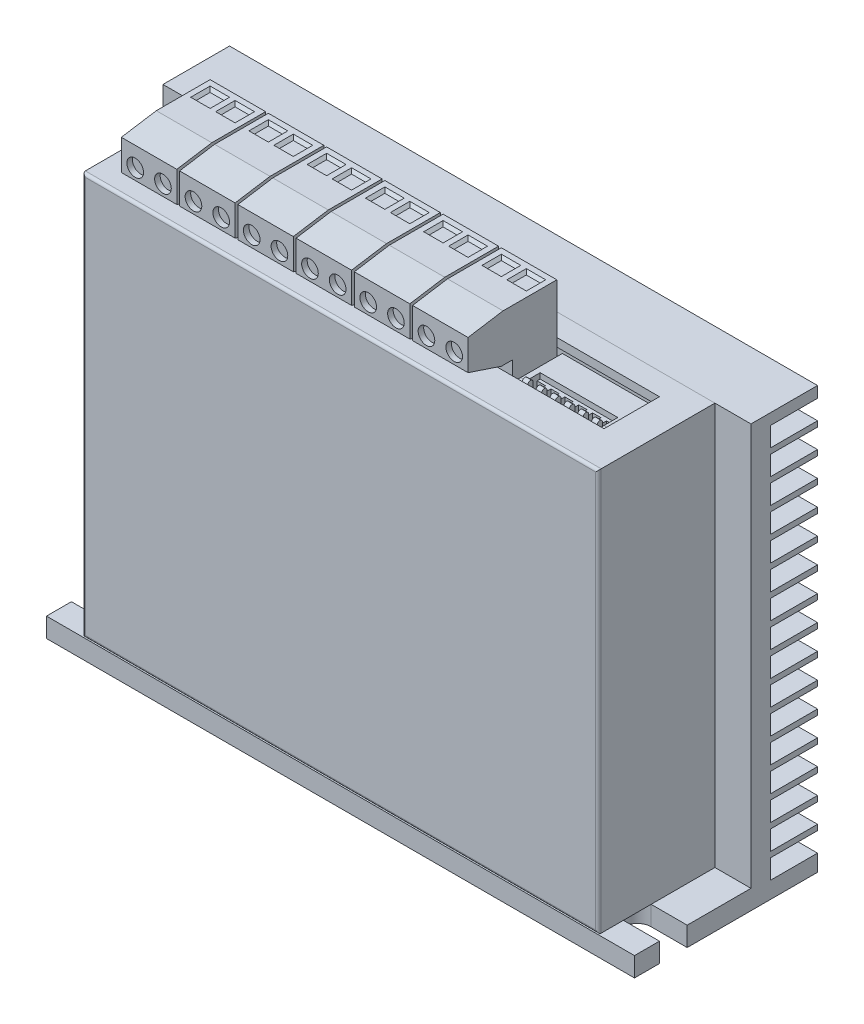
SolidWorks part; units mm, degrees
ref_plane "Спереди" through (0, 0, 0) normal (0, 0, 1) x (1, 0, 0)
ref_plane "Сверху" through (0, 0, 0) normal (0, 1, 0) x (1, 0, 0)
ref_plane "Справа" through (0, 0, 0) normal (1, 0, 0) x (0, 0, -1)
sketch "Эскиз1" plane through (0, 0, 0) normal (0, 0, 1) x (1, 0, 0)
  line L1 (-53, 0) -> (53, 0)
  line L2 (-53, 0) -> (-53, 76)
  line L3 (-53, 76) -> (53, 76)
  line L4 (53, 0) -> (53, 76)
  point P4 (0, 0)
  dimension "D1" = 76
  dimension "D2" = 106
extrude "Бобышка-Вытянуть1" add sketch "Эскиз1" along normal blind 33
sketch "Эскиз2" plane through (0, 0, 33) normal (0, 0, 1) x (1, 0, 0)
  line L0 (53, 0) -> (53, 76) construction
  line L1 (-53, 76) -> (53, 76)
  line L2 (-53, 76) -> (-53, 3.5)
  line L3 (-53, 3.5) -> (53, 3.5)
  line L4 (53, 76) -> (53, 3.5)
  line L5 (-53, 0) -> (53, 0) construction
  dimension "D1" = 3.5
extrude "Вырез-Вытянуть1" cut sketch "Эскиз2" against normal offset from surface (21 mm away) 12 up to face at (0, 38, 0)
sketch "Эскиз3" plane through (53, 0, 0) normal (1, 0, 0) x (0, 0, -1)
  line L0 (0, 0) -> (0, 76) construction
  line L1 (0, 3) -> (-8.5, 3)
  line L2 (0, 3) -> (0, 6.5)
  line L3 (0, 6.5) -> (-8.5, 6.5)
  line L4 (-8.5, 3) -> (-8.5, 6.5)
  line L5 (-33, 0) -> (0, 0) construction
  line L6 (-12, 3.5) -> (-12, 76) construction
  line L7 (0, 7.5) -> (-8.5, 7.5)
  line L8 (0, 7.5) -> (0, 11)
  line L9 (0, 11) -> (-8.5, 11)
  line L10 (-8.5, 7.5) -> (-8.5, 11)
  line L11 (0, 12) -> (-8.5, 12)
  line L12 (0, 12) -> (0, 15.5)
  line L13 (0, 15.5) -> (-8.5, 15.5)
  line L14 (-8.5, 12) -> (-8.5, 15.5)
  line L15 (0, 16.5) -> (-8.5, 16.5)
  line L16 (0, 16.5) -> (0, 20)
  line L17 (0, 20) -> (-8.5, 20)
  line L18 (-8.5, 16.5) -> (-8.5, 20)
  line L19 (0, 21) -> (-8.5, 21)
  line L20 (0, 21) -> (0, 24.5)
  line L21 (0, 24.5) -> (-8.5, 24.5)
  line L22 (-8.5, 21) -> (-8.5, 24.5)
  line L23 (0, 25.5) -> (-8.5, 25.5)
  line L24 (0, 25.5) -> (0, 29)
  line L25 (0, 29) -> (-8.5, 29)
  line L26 (-8.5, 25.5) -> (-8.5, 29)
  line L27 (0, 30) -> (-8.5, 30)
  line L28 (0, 30) -> (0, 33.5)
  line L29 (0, 33.5) -> (-8.5, 33.5)
  line L30 (-8.5, 30) -> (-8.5, 33.5)
  line L31 (0, 34.5) -> (-8.5, 34.5)
  line L32 (0, 34.5) -> (0, 38)
  line L33 (0, 38) -> (-8.5, 38)
  line L34 (-8.5, 34.5) -> (-8.5, 38)
  line L35 (0, 39) -> (-8.5, 39)
  line L36 (0, 39) -> (0, 42.5)
  line L37 (0, 42.5) -> (-8.5, 42.5)
  line L38 (-8.5, 39) -> (-8.5, 42.5)
  line L39 (0, 43.5) -> (-8.5, 43.5)
  line L40 (0, 43.5) -> (0, 47)
  line L41 (0, 47) -> (-8.5, 47)
  line L42 (-8.5, 43.5) -> (-8.5, 47)
  line L43 (0, 48) -> (-8.5, 48)
  line L44 (0, 48) -> (0, 51.5)
  line L45 (0, 51.5) -> (-8.5, 51.5)
  line L46 (-8.5, 48) -> (-8.5, 51.5)
  line L47 (0, 52.5) -> (-8.5, 52.5)
  line L48 (0, 52.5) -> (0, 56)
  line L49 (0, 56) -> (-8.5, 56)
  line L50 (-8.5, 52.5) -> (-8.5, 56)
  line L51 (0, 57) -> (-8.5, 57)
  line L52 (0, 57) -> (0, 60.5)
  line L53 (0, 60.5) -> (-8.5, 60.5)
  line L54 (-8.5, 57) -> (-8.5, 60.5)
  line L55 (0, 61.5) -> (-8.5, 61.5)
  line L56 (0, 61.5) -> (0, 65)
  line L57 (0, 65) -> (-8.5, 65)
  line L58 (-8.5, 61.5) -> (-8.5, 65)
  line L59 (0, 66) -> (-8.5, 66)
  line L60 (0, 66) -> (0, 69.5)
  line L61 (0, 69.5) -> (-8.5, 69.5)
  line L62 (-8.5, 66) -> (-8.5, 69.5)
  line L63 (0, 70.5) -> (-8.5, 70.5)
  line L64 (0, 70.5) -> (0, 74)
  line L65 (0, 74) -> (-8.5, 74)
  line L66 (-8.5, 70.5) -> (-8.5, 74)
  dimension "D1" = 3.5
  dimension "D2" = 3
  dimension "D3" = 3.5
  dimension "D5" = 4.5
  dimension "D4" = 16
extrude "Вырез-Вытянуть2" cut sketch "Эскиз3" against normal through all
sketch "Эскиз5" plane through (0, 0, 12) normal (0, 0, 1) x (1, 0, 0)
  line L0 (53, 76) -> (-53, 76) construction
  line L1 (-46.5, 76) -> (46.5, 76)
  line L2 (-46.5, 76) -> (-46.5, 3.5)
  line L3 (-46.5, 3.5) -> (46.5, 3.5)
  line L4 (46.5, 76) -> (46.5, 3.5)
  line L5 (-53, 3.5) -> (53, 3.5) construction
  point P8 (0, 3.5)
  dimension "D1" = 93
extrude "Бобышка-Вытянуть2" add sketch "Эскиз5" along normal up to surface (21 mm away) separate body up to face at (0, 1.75, 33)
sketch "Эскиз6" plane through (0, 0, 0) normal (0, -1, 0) x (1, 0, 0)
  line L0 (-53, 26) -> (-46.5, 26) construction
  line L1 (-53, 33) -> (-53, 0) construction
  line L2 (-53, 28.5) -> (-46.5, 28.5)
  line L3 (-53, 23.5) -> (-46.5, 23.5)
  line L4 (53, 26) -> (46.5, 26) construction
  line L5 (53, 33) -> (53, 0) construction
  line L6 (53, 23.5) -> (46.5, 23.5)
  line L7 (53, 28.5) -> (46.5, 28.5)
  line L8 (-53, 33) -> (53, 33) construction
  arc A0 (-53, 28.5) -> (-53, 23.5) centre (-53, 26) ccw
  arc A1 (-46.5, 23.5) -> (-46.5, 28.5) centre (-46.5, 26) ccw
  arc A2 (53, 23.5) -> (53, 28.5) centre (53, 26) ccw
  arc A3 (46.5, 28.5) -> (46.5, 23.5) centre (46.5, 26) ccw
  point P4 (-49.75, 26)
  point P9 (49.75, 26)
  dimension "D1" = 5
  dimension "D2" = 9
  dimension "D3" = 4.5
extrude "Вырез-Вытянуть3" cut sketch "Эскиз6" against normal up to next (3.5 mm away)
sketch "Эскиз7" plane through (0, 0, 33) normal (0, 0, 1) x (1, 0, 0)
  line L0 (-46.5, 76) -> (46.5, 76) construction
  line L1 (40.5, 13) -> (-40.5, 13) construction
  line L2 (40.5, 13) -> (40.5, 61) construction
  line L3 (40.5, 61) -> (-40.5, 61) construction
  line L4 (-40.5, 13) -> (-40.5, 61) construction
  line L5 (-46.5, 3.5) -> (-46.5, 76) construction
  circle A0 centre (-40.5, 61) radius 2
  circle A1 centre (-40.5, 13) radius 2
  circle A2 centre (40.5, 61) radius 2
  circle A3 centre (40.5, 13) radius 2
  point P0 (0, 13)
  dimension "D1" = 4
  dimension "D2" = 44
  dimension "D3" = 13
  dimension "D4" = 4
extrude "Вырез-Вытянуть4" [suppressed] cut sketch "Эскиз7" against normal blind 10
shell "Оболочка2" thickness 1.5
sketch "Эскиз8" plane through (0, 76, 0) normal (0, 1, 0) x (1, 0, 0)
  line L0 (-46.5, -33) -> (46.5, -33) construction
  line L1 (-40.5, -16) -> (40.5, -16)
  line L2 (-40.5, -16) -> (-40.5, -26)
  line L3 (-40.5, -26) -> (40.5, -26)
  line L4 (40.5, -16) -> (40.5, -26)
  line L5 (46.5, -33) -> (46.5, -12) construction
  point P8 (0, -16)
  dimension "D1" = 7
  dimension "D2" = 10
  dimension "D3" = 6
extrude "Вырез-Вытянуть5" cut sketch "Эскиз8" against normal up to next (1.5 mm away)
fillet "Скругление1" radius 0.5 4 edges at (-46.5, 39.75, 33) (0, 76, 33) (46.5, 39.75, 33) (0, 3.5, 33)
sketch "Эскиз9" plane through (0, 0, 33) normal (0, 0, 1) x (1, 0, 0)
  line L0 (46.5, 76) -> (46.5, 3.5) construction
  line L1 (-46.5, 76) -> (46.5, 76) construction
  circle A0 centre (38.5, 56) radius 1.5
  circle A1 centre (38.5, 51) radius 1.5
  dimension "D1" = 3
  dimension "D2" = 2
  dimension "D3" = 8
  dimension "D4" = 20
extrude "Вырез-Вытянуть6" [suppressed] cut sketch "Эскиз9" against normal up to next
sketch "Эскиз11" plane through (0, 74.5, 0) normal (0, -1, 0) x (1, 0, 0)
  line L0 (40.5, 16) -> (-40.5, 16) construction
  line L1 (23.5, 16.5) -> (39.5, 16.5)
  line L2 (23.5, 16.5) -> (23.5, 25.5)
  line L3 (23.5, 25.5) -> (39.5, 25.5)
  line L4 (39.5, 16.5) -> (39.5, 25.5)
  line L5 (40.5, 26) -> (40.5, 16) construction
  line L6 (-40.5, 26) -> (40.5, 26) construction
  dimension "D1" = 0.5
  dimension "D2" = 1
  dimension "D3" = 0.5
  dimension "D4" = 16
extrude "Бобышка-Вытянуть3" add sketch "Эскиз11" along normal blind 10 separate body
sketch "Эскиз12" plane through (0, 74.5, 0) normal (0, 1, 0) x (1, 0, 0)
  line L0 (39.5, -25.5) -> (23.5, -25.5) construction
  line L1 (24.5, -25.5) -> (38.5, -25.5)
  line L2 (24.5, -25.5) -> (24.5, -21.5)
  line L3 (24.5, -21.5) -> (38.5, -21.5)
  line L4 (38.5, -25.5) -> (38.5, -21.5)
  line L5 (39.5, -16.5) -> (39.5, -25.5) construction
  line L6 (23.5, -25.5) -> (23.5, -16.5) construction
  line L7 (23.5, -16.5) -> (39.5, -16.5) construction
  dimension "D1" = 1
  dimension "D2" = 1
  dimension "D3" = 5
extrude "Вырез-Вытянуть7" cut sketch "Эскиз12" against normal blind 1
sketch "Эскиз13" plane through (0, 73.5, 0) normal (0, 1, 0) x (1, 0, 0)
  line L0 (27, -25.5) -> (28.5, -25.5)
  line L1 (24.5, -25.5) -> (26, -25.5)
  line L2 (24.5, -25.5) -> (24.5, -22.0537)
  line L3 (24.5, -22.0537) -> (26, -22.0537)
  line L4 (26, -25.5) -> (26, -22.0537)
  line L5 (27, -25.5) -> (27, -22.0537)
  line L6 (27, -22.0537) -> (28.5, -22.0537)
  line L7 (28.5, -25.5) -> (28.5, -22.0537)
  line L8 (29.5, -25.5) -> (31, -25.5)
  line L9 (29.5, -25.5) -> (29.5, -22.0537)
  line L10 (29.5, -22.0537) -> (31, -22.0537)
  line L11 (31, -25.5) -> (31, -22.0537)
  line L12 (32, -25.5) -> (33.5, -25.5)
  line L13 (32, -25.5) -> (32, -22.0537)
  line L14 (32, -22.0537) -> (33.5, -22.0537)
  line L15 (33.5, -25.5) -> (33.5, -22.0537)
  line L16 (34.5, -25.5) -> (36, -25.5)
  line L17 (34.5, -25.5) -> (34.5, -22.0537)
  line L18 (34.5, -22.0537) -> (36, -22.0537)
  line L19 (36, -25.5) -> (36, -22.0537)
  line L20 (37, -25.5) -> (38.5, -25.5)
  line L21 (37, -25.5) -> (37, -22.0537)
  line L22 (37, -22.0537) -> (38.5, -22.0537)
  line L23 (38.5, -25.5) -> (38.5, -22.0537)
  dimension "D2" = 1.5
  dimension "D1" = 6
extrude "Вырез-Вытянуть8" cut sketch "Эскиз13" against normal blind 2
fillet "s" radius 1.5 2 edges at (24, 74.5, 25.5) (39, 74.5, 25.5)
chamfer "Фаска1" distance 2 angle 45 5 edges at (36.5, 73.5, 25.5) (34, 73.5, 25.5) (31.5, 73.5, 25.5) (29, 73.5, 25.5) (26.5, 73.5, 25.5)
sketch "Эскиз14" plane through (24.5, 0, 0) normal (1, 0, 0) x (0, 0, -1)
  line L0 (-24.5, 70.9) -> (-24.5, 74.9) construction
  line L1 (-25, 70.9) -> (-25, 74.9)
  line L2 (-24, 70.9) -> (-24, 74.9)
  line L6 (-25.5, 71.5) -> (-22.0537, 71.5) construction
  line L7 (-25.5, 64.5) -> (-25.5, 73) construction
  arc A0 (-25, 70.9) -> (-24, 70.9) centre (-24.5, 70.9) ccw
  arc A1 (-24, 74.9) -> (-25, 74.9) centre (-24.5, 74.9) ccw
  point P2 (-24.5, 72.9)
  dimension "D1" = 1
  dimension "D2" = 4
  dimension "D3" = 0.5
  dimension "D5" = 0.6
extrude "Бобышка-Вытянуть4" add sketch "Эскиз14" along normal blind 1 from offset 0.25
pattern_linear "Линейный массив1" count 6 spacing 2.5 along (1, 0, 0) of "Бобышка-Вытянуть4"
sketch "Эскиз15" plane through (-40.5, 0, 0) normal (1, 0, 0) x (0, 0, -1)
  line L0 (-25, 74) -> (-25, 77.5)
  line L1 (-33, 79.5) -> (-27, 77.5)
  line L2 (-33, 79.5) -> (-33, 85)
  line L3 (-32.5, 76) -> (-12, 76) construction
  line L4 (-17, 86) -> (-17, 74)
  line L5 (-17, 74) -> (-25, 74)
  line L7 (-33, 4) -> (-33, 75.5) construction
  line L8 (-27, 77.5) -> (-25, 77.5)
  line L9 (-17, 86) -> (-26.6983, 86)
  line L10 (-26.6983, 86) -> (-33, 85)
  dimension "D1" = 16
  dimension "D2" = 10
  dimension "D3" = 8
  dimension "D4" = 2
  dimension "D5" = 1.5
  dimension "D6" = 2
  dimension "D7" = 2
  dimension "D8" = 1
extrude "Бобышка-Вытянуть5" add sketch "Эскиз15" along normal blind 10 from offset 1 separate body
sketch "Эскиз16" plane through (0, 0, 17) normal (0, 0, -1) x (-1, 0, 0)
  line L1 (30.496, 85) -> (33.5, 85)
  line L2 (30.496, 85) -> (30.496, 74)
  line L3 (30.496, 74) -> (33.5, 74)
  line L4 (33.5, 85) -> (33.5, 74)
  line L5 (35.5, 85) -> (38.504, 85)
  line L6 (35.5, 85) -> (35.5, 74)
  line L7 (35.5, 74) -> (38.504, 74)
  line L8 (38.504, 85) -> (38.504, 74)
  line L9 (38.504, 85) -> (39.5, 85) construction
  line L10 (39.5, 74) -> (39.5, 86) construction
  line L11 (30.496, 85) -> (29.5, 85) construction
  line L12 (29.5, 74) -> (29.5, 86) construction
  line L13 (29.5, 86) -> (39.5, 86) construction
  line L14 (53, 74) -> (-53, 74) construction
  dimension "D1" = 1
  dimension "D2" = 0.996
  dimension "D3" = 2
extrude "Вырез-Вытянуть9" cut sketch "Эскиз16" against normal blind 1
sketch "Эскиз17" plane through (0, 86, 0) normal (0, 1, 0) x (1, 0, 0)
  line L0 (-29.5, -17) -> (-39.5, -17) construction
  line L1 (-38.5, -18) -> (-35, -18)
  line L2 (-38.5, -18) -> (-38.5, -21.5)
  line L3 (-38.5, -21.5) -> (-35, -21.5)
  line L4 (-35, -18) -> (-35, -21.5)
  line L5 (-34, -18) -> (-30.5, -18)
  line L6 (-34, -18) -> (-34, -21.5)
  line L7 (-34, -21.5) -> (-30.5, -21.5)
  line L8 (-30.5, -18) -> (-30.5, -21.5)
  line L9 (-39.5, -17) -> (-39.5, -26.6983) construction
  line L10 (-29.5, -17) -> (-29.5, -26.6983) construction
  dimension "D1" = 1
  dimension "D2" = 1
  dimension "D3" = 1
  dimension "D4" = 1
extrude "Вырез-Вытянуть11" cut sketch "Эскиз17" against normal blind 0.5 draft 45
sketch "Эскиз18" plane through (0, 0, 33) normal (0, 0, 1) x (1, 0, 0)
  line L0 (-39.5, 81.5) -> (-37, 81.5) construction
  line L1 (-39.5, 85) -> (-39.5, 79.5) construction
  line L2 (-37, 81.5) -> (-32, 81.5) construction
  line L4 (-32, 81.5) -> (-29.5, 81.5) construction
  line L5 (-29.5, 85) -> (-29.5, 79.5) construction
  line L6 (-29.5, 79.5) -> (-39.5, 79.5) construction
  circle A0 centre (-37, 81.5) radius 1.5
  circle A1 centre (-32, 81.5) radius 1.5
  dimension "D1" = 3
  dimension "D2" = 2
  dimension "D3" = 5
extrude "Вырез-Вытянуть12" cut sketch "Эскиз18" against normal blind 1
pattern_linear "Линейный массив2" count 6 spacing 10.5 along (1, 0, 0) of bodies 119
